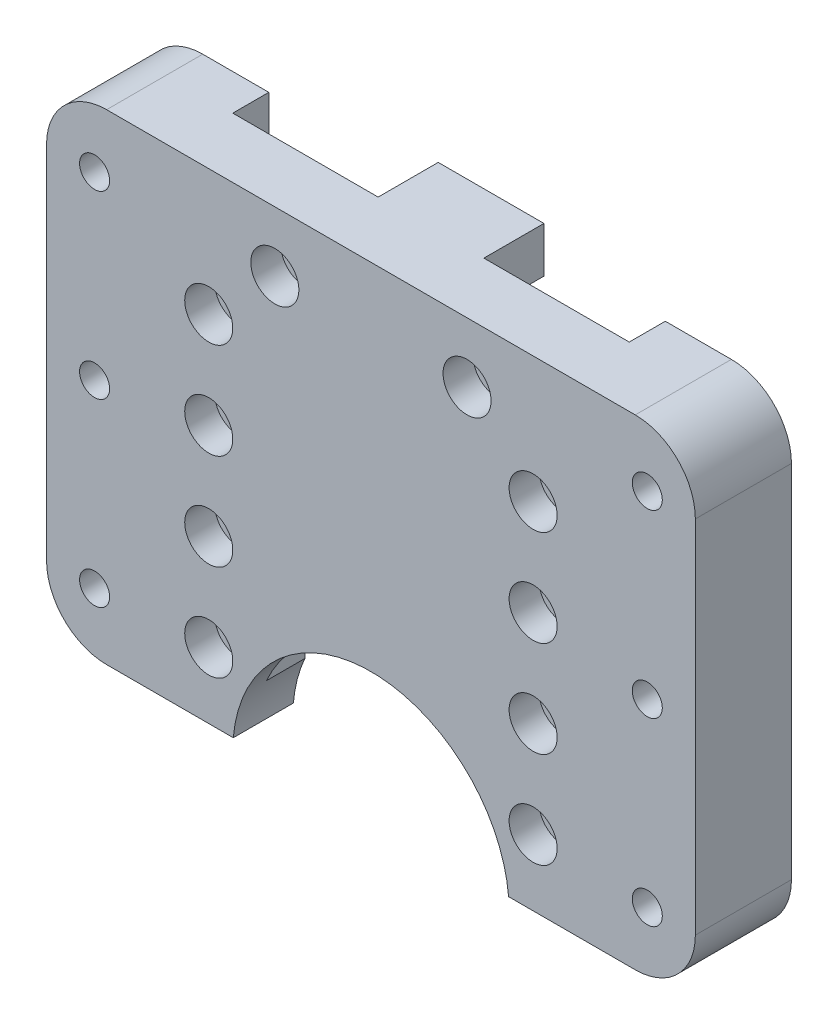
SolidWorks part; units mm, degrees
material "ABS"
ref_plane "Płaszczyzna przednia" through (0, 0, 0) normal (0, 0, 1) x (1, 0, 0)
ref_plane "Płaszczyzna górna" through (0, 0, 0) normal (0, 1, 0) x (1, 0, 0)
ref_plane "Płaszczyzna prawa" through (0, 0, 0) normal (1, 0, 0) x (0, 0, -1)
sketch "Szkic1" plane through (0, 0, 0) normal (0, 0, 1) x (1, 0, 0)
  line L1 (-17, -20) -> (17, -20)
  line L2 (-17, -20) -> (-17, 20)
  line L3 (-17, 20) -> (17, 20)
  line L4 (17, -20) -> (17, 20)
  line L5 (-17, -20) -> (17, 20) construction
  line L6 (-17, 20) -> (17, -20) construction
  point P0 (0, 0)
  dimension "D1" = 40
  dimension "D2" = 34
extrude "Dodanie-wyciągnięcie1" add sketch "Szkic1" along normal blind 5
sketch "Szkic2" plane through (0, 0, 5) normal (0, 0, 1) x (1, 0, 0)
  line L0 (17, 20) -> (-17, 20) construction
  line L1 (0, 0) -> (0, 20) construction
  circle A0 centre (8, 15) radius 1.25
  circle A1 centre (13.5, 9.5) radius 1.25
  circle A2 centre (13.5, 1.5) radius 1.25
  circle A3 centre (13.5, -6.5) radius 1.25
  circle A4 centre (13.5, -14.5) radius 1.25
  dimension "D1" = 2.5
  dimension "D2" = 5.5
  dimension "D3" = 5.5
  dimension "D4" = 8
  dimension "D5" = 8
  dimension "D6" = 8
  dimension "D7" = 5
  dimension "D8" = 8
extrude "Wytnij-wyciągnięcie1" cut sketch "Szkic2" against normal blind 5
sketch "Szkic3" plane through (0, 0, 5) normal (0, 0, 1) x (1, 0, 0)
  line L0 (-17, -20) -> (17, -20) construction
  circle A0 centre (0, -21) radius 11.5
  point P4 (0, 0)
  dimension "D1" = 1
  dimension "D2" = 23
extrude "Wytnij-wyciągnięcie2" cut sketch "Szkic3" against normal blind 5
sketch "Szkic4" plane through (0, 0, 5) normal (0, 0, 1) x (1, 0, 0)
  circle A0 centre (8, 15) radius 2
  circle A1 centre (13.5, 9.5) radius 2
  circle A2 centre (13.5, 1.5) radius 2
  circle A3 centre (13.5, -6.5) radius 2
  circle A4 centre (13.5, -14.5) radius 2
  dimension "D1" = 4
extrude "Wytnij-wyciągnięcie3" cut sketch "Szkic4" against normal blind 2.5
mirror "Lustro1" about plane through (0, 0, 0) normal (1, 0, 0) of "Wytnij-wyciągnięcie3", "Wytnij-wyciągnięcie1"
sketch "Szkic5" plane through (0, 0, 0) normal (0, 0, -1) x (-1, 0, 0)
  line L0 (0, 0) -> (0, -20) construction
  line L1 (-10.5, 12) -> (10.5, 12)
  line L2 (-10.5, 12) -> (-10.5, -18)
  line L3 (-10.5, -18) -> (10.5, -18)
  line L4 (10.5, 12) -> (10.5, -18)
  circle A0 centre (-8, 15) radius 1.25 construction
  dimension "D1" = 30
  dimension "D2" = 21
  dimension "D3" = 3
extrude "Wytnij-wyciągnięcie4" cut sketch "Szkic5" against normal blind 3.2
sketch "Szkic6" plane through (0, 0, 5) normal (0, 0, 1) x (1, 0, 0)
  line L0 (-17, 20) -> (-17, -20) construction
  line L5 (-17, 20) -> (-27, 20)
  line L6 (-17, 20) -> (-17, -20)
  line L7 (-17, -20) -> (-27, -20)
  line L8 (-27, 20) -> (-27, -20)
  circle A0 centre (-23, -15) radius 1.25
  circle A1 centre (-23, 0) radius 1.25
  circle A2 centre (-23, 15) radius 1.25
  dimension "D1" = 2.5
  dimension "D2" = 6
  dimension "D3" = 15
  dimension "D4" = 15
  dimension "D5" = 40
  dimension "D6" = 10
extrude "Dodanie-wyciągnięcie2" add sketch "Szkic6" against normal up to surface (5 mm away) up to face at (0, -4.8539, 0)
fillet "Zaokrąglenie1" radius 5 2 edges at (-27, 20, 2.5) (-27, -20, 2.5)
mirror "Lustro2" about plane through (0, 0, 0) normal (1, 0, 0) of "Zaokrąglenie1", "Dodanie-wyciągnięcie2"
sketch "Szkic7" plane through (0, 0, 0) normal (0, 0, -1) x (-1, 0, 0)
  line L0 (-22, 20) -> (22, 20) construction
  line L1 (-4.4, 20) -> (4.4, 20)
  line L2 (-4.4, 20) -> (-4.4, 16.2)
  line L3 (-4.4, 16.2) -> (4.4, 16.2)
  line L4 (4.4, 20) -> (4.4, 16.2)
  line L5 (0, 0) -> (0, 12) construction
  line L6 (10.5, 12) -> (-10.5, 12) construction
  dimension "D1" = 3.8
  dimension "D2" = 8.8
extrude "Dodanie-wyciągnięcie3" add sketch "Szkic7" along normal blind 5
sketch "Szkic8" plane through (0, 0, 0) normal (0, 0, -1) x (-1, 0, 0)
  line L2 (-16.5, 20) -> (-16.5, -20)
  line L6 (-22, 20) -> (-4.4, 20) construction
  line L10 (16.5, 20) -> (16.5, -20)
  line L14 (4.4, 20) -> (22, 20) construction
  line L16 (0, 0) -> (0, -20) construction
  line L29 (-4.4, 16.2) -> (-4.4, 20)
  line L30 (-4.4, 20) -> (-22, 20)
  line L31 (-27, 15) -> (-27, -15)
  line L32 (-22, -20) -> (-11.4564, -20)
  line L33 (-10.5, -16.3096) -> (-10.5, 12)
  line L34 (-10.5, 12) -> (10.5, 12)
  line L35 (10.5, 12) -> (10.5, -16.3096)
  line L36 (11.4564, -20) -> (22, -20)
  line L37 (27, -15) -> (27, 15)
  line L38 (22, 20) -> (4.4, 20)
  line L39 (4.4, 20) -> (4.4, 16.2)
  line L40 (4.4, 16.2) -> (-4.4, 16.2)
  line L41 (-4.4, 16.2) -> (-4.4, 20)
  line L42 (-4.4, 20) -> (-22, 20)
  line L43 (-27, 15) -> (-27, -15)
  line L44 (-22, -20) -> (-11.4564, -20)
  line L45 (-10.5, -16.3096) -> (-10.5, 12)
  line L46 (-10.5, 12) -> (10.5, 12)
  line L47 (10.5, 12) -> (10.5, -16.3096)
  line L48 (11.4564, -20) -> (22, -20)
  line L49 (27, -15) -> (27, 15)
  line L50 (22, 20) -> (4.4, 20)
  line L51 (4.4, 20) -> (4.4, 16.2)
  line L52 (4.4, 16.2) -> (-4.4, 16.2)
  circle A0 centre (23, 15) radius 1.25 construction
  circle A1 centre (23, 0) radius 1.25 construction
  circle A2 centre (23, -15) radius 1.25 construction
  circle A3 centre (-23, -15) radius 1.25 construction
  circle A4 centre (-23, 0) radius 1.25 construction
  circle A5 centre (-23, 15) radius 1.25 construction
  arc A6 (-22, 20) -> (-27, 15) centre (-22, 15) ccw
  arc A7 (-27, -15) -> (-22, -20) centre (-22, -15) ccw
  arc A8 (-10.5, -16.3096) -> (-11.4564, -20) centre (0, -21) ccw
  arc A9 (11.4564, -20) -> (10.5, -16.3096) centre (0, -21) ccw
  arc A10 (22, -20) -> (27, -15) centre (22, -15) ccw
  arc A11 (27, 15) -> (22, 20) centre (22, 15) ccw
  arc A12 (-22, 20) -> (-27, 15) centre (-22, 15) ccw
  arc A13 (-27, -15) -> (-22, -20) centre (-22, -15) ccw
  arc A14 (-10.5, -16.3096) -> (-11.4564, -20) centre (0, -21) ccw
  arc A15 (11.4564, -20) -> (10.5, -16.3096) centre (0, -21) ccw
  arc A16 (22, -20) -> (27, -15) centre (22, -15) ccw
  arc A17 (27, 15) -> (22, 20) centre (22, 15) ccw
  circle A18 centre (23, 15) radius 1.25
  circle A19 centre (23, 0) radius 1.25
  circle A20 centre (23, -15) radius 1.25
  circle A21 centre (-23, -15) radius 1.25
  circle A22 centre (-23, 0) radius 1.25
  circle A23 centre (-23, 15) radius 1.25
  line M25 (-4.4, 20) -> (-22, 20)
  arc M26 (-22, 20) -> (-27, 15) centre (-22, 15) ccw
  line M27 (-27, 15) -> (-27, -15)
  arc M28 (-27, -15) -> (-22, -20) centre (-22, -15) ccw
  line M29 (-22, -20) -> (-11.4564, -20)
  line M35 (11.4564, -20) -> (22, -20)
  arc M36 (22, -20) -> (27, -15) centre (22, -15) ccw
  line M37 (27, -15) -> (27, 15)
  arc M38 (27, 15) -> (22, 20) centre (22, 15) ccw
  line M39 (22, 20) -> (4.4, 20)
  circle M52 centre (23, 0) radius 1.25
  circle M53 centre (23, 15) radius 1.25
  circle M54 centre (23, -15) radius 1.25
  circle M55 centre (-23, 15) radius 1.25
  circle M56 centre (-23, 0) radius 1.25
  circle M57 centre (-23, -15) radius 1.25
  dimension "D1" = 40
  dimension "D2" = 0
  dimension "D3" = 40
  dimension "D4" = 33
extrude "Dodanie-wyciągnięcie4" add sketch "Szkic8" along normal blind 3 contours L2 M25 M26 M27 M28 M29 M56 M57 M55 | L10 M39 M35 M36 M37 M38 M52 M54 M53
sketch "Szkic9" plane through (0, 0, -3) normal (0, 0, -1) x (-1, 0, 0)
  line L1 (-23, 12.5751) -> (-20.9, 13.7876)
  line L2 (-20.9, 13.7876) -> (-20.9, 16.2124)
  line L3 (-20.9, 16.2124) -> (-23, 17.4249)
  line L4 (-23, 17.4249) -> (-25.1, 16.2124)
  line L5 (-25.1, 16.2124) -> (-25.1, 13.7876)
  line L6 (-25.1, 13.7876) -> (-23, 12.5751)
  circle A0 centre (-23, 15) radius 2.1 construction
  point P1 (0, 0)
  dimension "D1" = 4.2
extrude "Wytnij-wyciągnięcie5" cut sketch "Szkic9" against normal blind 3
pattern_linear "Szyk liniowy1" count 2 spacing 46 along (-1, 0, 0) count 3 spacing 15 along (0, -1, 0) of "Wytnij-wyciągnięcie5"
chamfer "Sfazowanie1" distance 2 angle 45 2 edges at (16.5, -20, -1.5) (-16.5, -20, -1.5)
